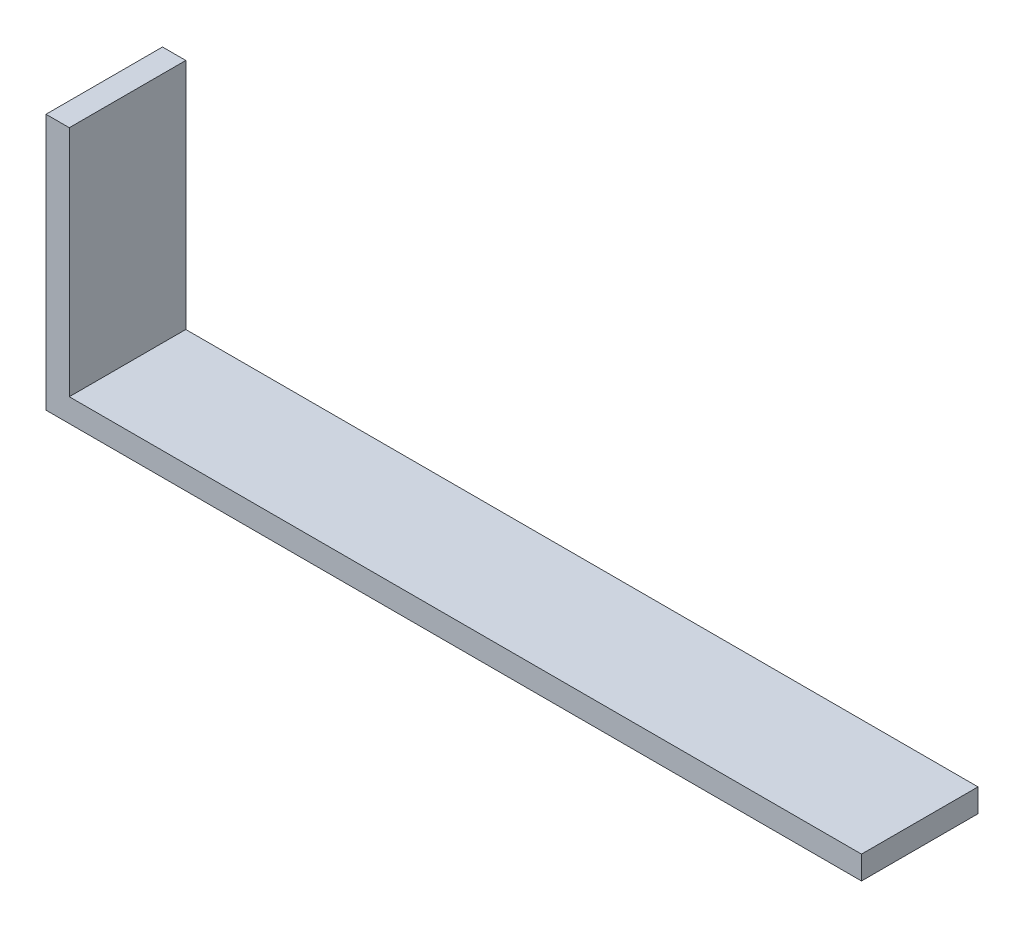
SolidWorks part; units mm, degrees
ref_plane "Front Plane" through (0, 0, 0) normal (0, 0, 1) x (1, 0, 0)
ref_plane "Top Plane" through (0, 0, 0) normal (0, 1, 0) x (1, 0, 0)
ref_plane "Right Plane" through (0, 0, 0) normal (1, 0, 0) x (0, 0, -1)
sketch "Sketch1" plane through (0, 0, 0) normal (0, 0, 1) x (1, 0, 0)
  line L0 (0, 5.9813) -> (0, -7.9887)
  line L1 (0, -7.9887) -> (44.45, -7.9887)
  line L2 (44.45, -7.9887) -> (44.45, -6.7187)
  line L3 (44.45, -6.7187) -> (1.27, -6.7187)
  line L4 (1.27, -6.7187) -> (1.27, 5.9813)
  line L5 (1.27, 5.9813) -> (0, 5.9813)
  dimension "D1" = 12.7
  dimension "D2" = 43.18
  dimension "D3" = 12.7
  dimension "D4" = 1.27
  dimension "D5" = 1.27
  dimension "D6" = 44.45
extrude "Boss-Extrude1" add sketch "Sketch1" along normal blind 6.35
